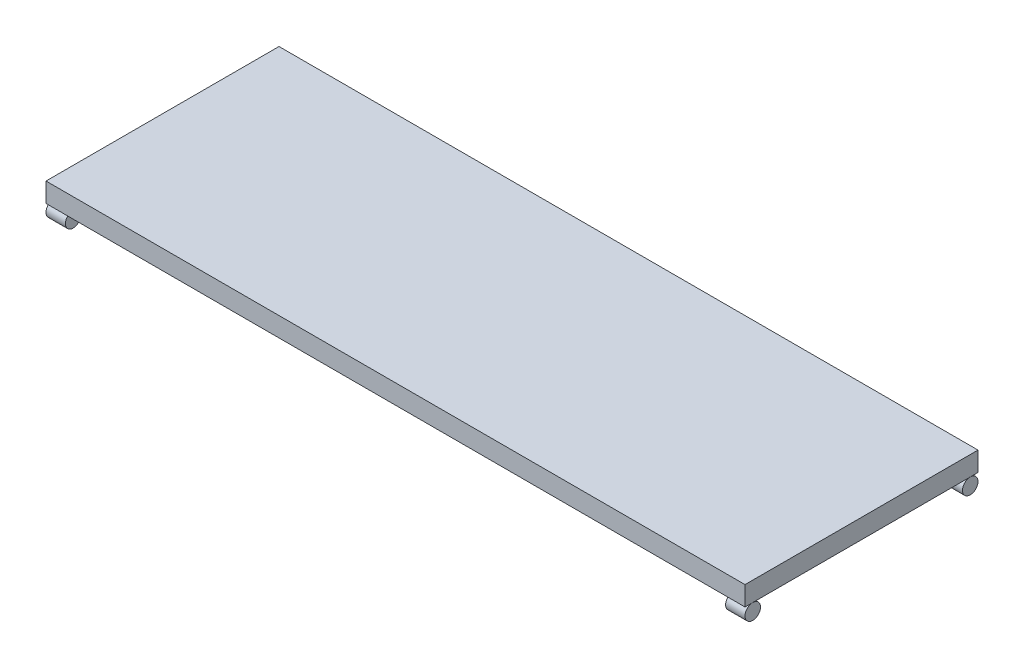
SolidWorks part; units mm, degrees
ref_plane "前视基准面" through (0, 0, 0) normal (0, 0, 1) x (1, 0, 0)
ref_plane "上视基准面" through (0, 0, 0) normal (0, 1, 0) x (1, 0, 0)
ref_plane "右视基准面" through (0, 0, 0) normal (1, 0, 0) x (0, 0, -1)
sketch "草图5" plane through (0, 0, 0) normal (0, 1, 0) x (1, 0, 0)
  line L1 (0, 0) -> (1800, 0)
  line L2 (0, 0) -> (0, 600)
  line L3 (0, 600) -> (1800, 600)
  line L4 (1800, 0) -> (1800, 600)
extrude "凸台-拉伸4" add sketch "草图5" along normal blind 50
sketch "草图6" plane through (0, 0, 0) normal (1, 0, 0) x (0, 0, -1)
  circle A0 centre (20, -20) radius 20
  circle A2 centre (580, -20) radius 20
extrude "凸台-拉伸5" add sketch "草图6" along normal blind 50 separate body
ref_plane "基准面1" through (1800, 0, 0) normal (1, 0, 0) x (0, 0, -1)
sketch "草图7" plane through (1800, 0, 0) normal (1, 0, 0) x (0, 0, -1)
  circle A0 centre (20, -20) radius 20
  circle A1 centre (580, -20) radius 20
extrude "凸台-拉伸6" add sketch "草图7" against normal blind 50 separate body
